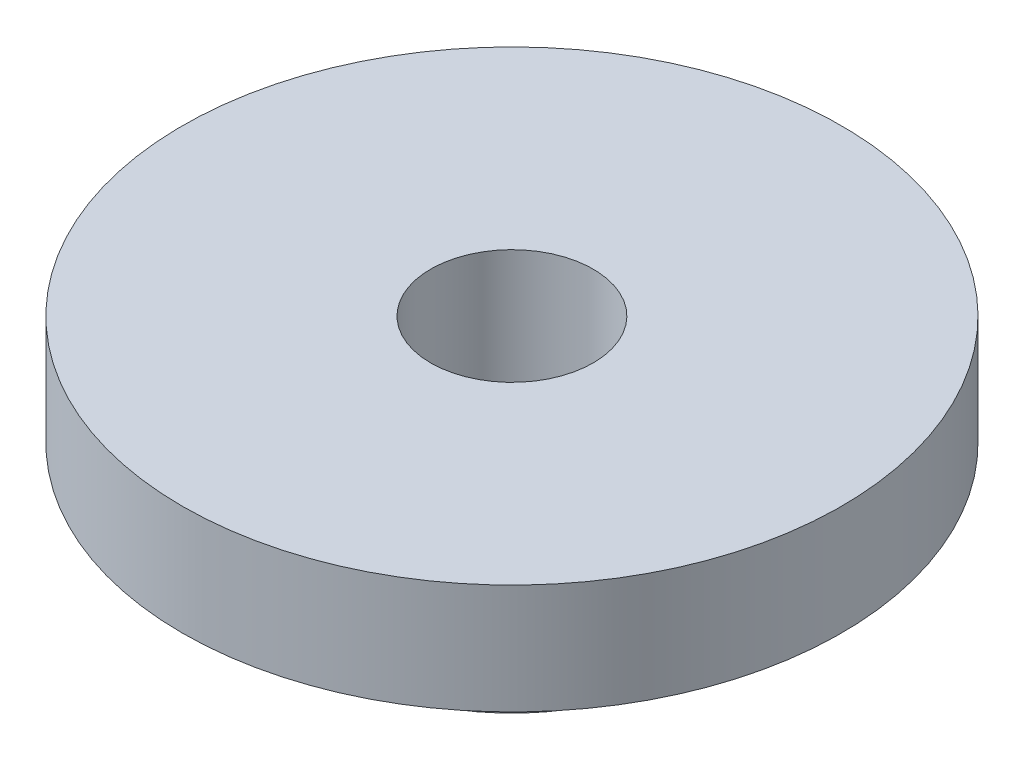
SolidWorks part; units mm, degrees
ref_plane "Front Plane" through (0, 0, 0) normal (0, 0, 1) x (1, 0, 0)
ref_plane "Top Plane" through (0, 0, 0) normal (0, 1, 0) x (1, 0, 0)
ref_plane "Right Plane" through (0, 0, 0) normal (1, 0, 0) x (0, 0, -1)
sketch "Sketch1" plane through (0, 0, 0) normal (0, 1, 0) x (1, 0, 0)
  circle A0 centre (0, 0) radius 4
  dimension "D1" = 8
extrude "Boss-Extrude1" add sketch "Sketch1" along normal blind 2.5
sketch "Sketch2" plane through (0, 2.5, 0) normal (0, 1, 0) x (1, 0, 0)
  circle A0 centre (0, 0) radius 7.5
  dimension "D1" = 15
extrude "Boss-Extrude2" add sketch "Sketch2" along normal blind 2.5
sketch "Sketch3" plane through (0, 5, 0) normal (0, 1, 0) x (1, 0, 0)
  circle A0 centre (0, 0) radius 1.85
  dimension "D1" = 3.7
extrude "Cut-Extrude1" cut sketch "Sketch3" against normal blind 18
